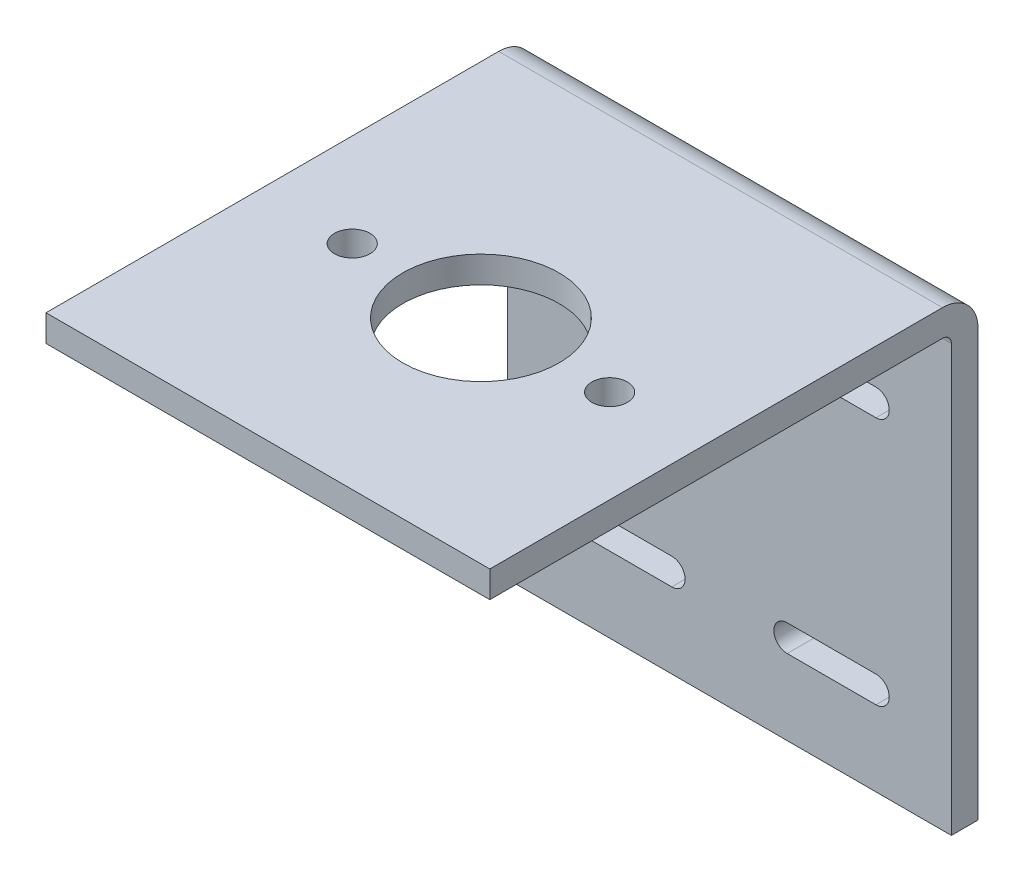
SolidWorks part; units mm, degrees
ref_plane "Front Plane" through (0, 0, 0) normal (0, 0, 1) x (1, 0, 0)
ref_plane "Top Plane" through (0, 0, 0) normal (0, 1, 0) x (1, 0, 0)
ref_plane "Right Plane" through (0, 0, 0) normal (1, 0, 0) x (0, 0, -1)
sketch "Sketch1" plane through (0, 0, 0) normal (0, 0, 1) x (1, 0, 0)
  line L1 (0, 0) -> (50, 0)
  line L2 (0, 0) -> (0, 52)
  line L3 (0, 52) -> (50, 52)
  line L4 (50, 0) -> (50, 52)
  dimension "D1" = 52
  dimension "D2" = 50
extrude "Boss-Extrude1" add sketch "Sketch1" along normal blind 3
sketch "Sketch2" plane through (0, 0, 3) normal (0, 0, 1) x (1, 0, 0)
  line L0 (50, 0) -> (50, 52) construction
  line L1 (0, 52) -> (50, 52)
  line L2 (0, 52) -> (0, 49)
  line L3 (0, 49) -> (50, 49)
  line L4 (50, 52) -> (50, 49)
  dimension "D1" = 3
extrude "Boss-Extrude2" add sketch "Sketch2" along normal blind 52
fillet "Fillet1" radius 4 1 edges at (25, 52, 0)
fillet "Fillet2" radius 1 1 edges at (25, 49, 3)
sketch "Sketch3" plane through (0, 52, 0) normal (0, 1, 0) x (1, 0, 0)
  line L0 (50, -55) -> (0, -55) construction
  line L1 (25, -53) -> (25, 49947) construction
  circle A0 centre (10.5, -31) radius 2
  circle A1 centre (39.5, -31) radius 2
  circle A2 centre (25, -31) radius 8.8
  point P8 (0, 0)
  point P9 (0, 0)
  point P12 (25, -55)
  dimension "D3" = 4
  dimension "D4" = 14.5
  dimension "D5" = 17.6
  dimension "D1" = 24
  dimension "D2" = 29
extrude "Cut-Extrude1" cut sketch "Sketch3" against normal up to next
sketch "Sketch6" plane through (0, 0, 3) normal (0, 0, 1) x (1, 0, 0)
  line L0 (0, 24) -> (20.2604, 24) construction
  line L2 (0, 48) -> (0, 0) construction
  line L3 (8.5, 38) -> (18.5, 38) construction
  line L4 (8.5, 39.5) -> (18.5, 39.5)
  line L5 (8.5, 36.5) -> (18.5, 36.5)
  line L6 (25, -951) -> (25, 49049) construction
  line L9 (0, 49) -> (50, 49) construction
  line L10 (41.5, 38) -> (31.5, 38) construction
  line L11 (41.5, 39.5) -> (31.5, 39.5)
  line L12 (41.5, 36.5) -> (31.5, 36.5)
  line L13 (8.5, 10) -> (18.5, 10) construction
  line L14 (8.5, 8.5) -> (18.5, 8.5)
  line L15 (8.5, 11.5) -> (18.5, 11.5)
  line L16 (41.5, 10) -> (31.5, 10) construction
  line L17 (41.5, 8.5) -> (31.5, 8.5)
  line L18 (41.5, 11.5) -> (31.5, 11.5)
  arc A0 (8.5, 39.5) -> (8.5, 36.5) centre (8.5, 38) ccw
  arc A1 (18.5, 36.5) -> (18.5, 39.5) centre (18.5, 38) ccw
  arc A4 (41.5, 39.5) -> (41.5, 36.5) centre (41.5, 38) cw
  arc A5 (31.5, 36.5) -> (31.5, 39.5) centre (31.5, 38) cw
  arc A6 (8.5, 8.5) -> (8.5, 11.5) centre (8.5, 10) cw
  arc A7 (18.5, 11.5) -> (18.5, 8.5) centre (18.5, 10) cw
  arc A8 (41.5, 8.5) -> (41.5, 11.5) centre (41.5, 10) ccw
  arc A9 (31.5, 11.5) -> (31.5, 8.5) centre (31.5, 10) ccw
  point P3 (0, 24)
  point P7 (13.5, 38)
  point P17 (25, 49)
  point P19 (36.5, 38)
  point P26 (13.5, 10)
  point P33 (36.5, 10)
  dimension "D2" = 1.5
  dimension "D1" = 10
  dimension "D3" = 14
  dimension "D4" = 13.5
extrude "Cut-Extrude2" cut sketch "Sketch6" against normal up to next
